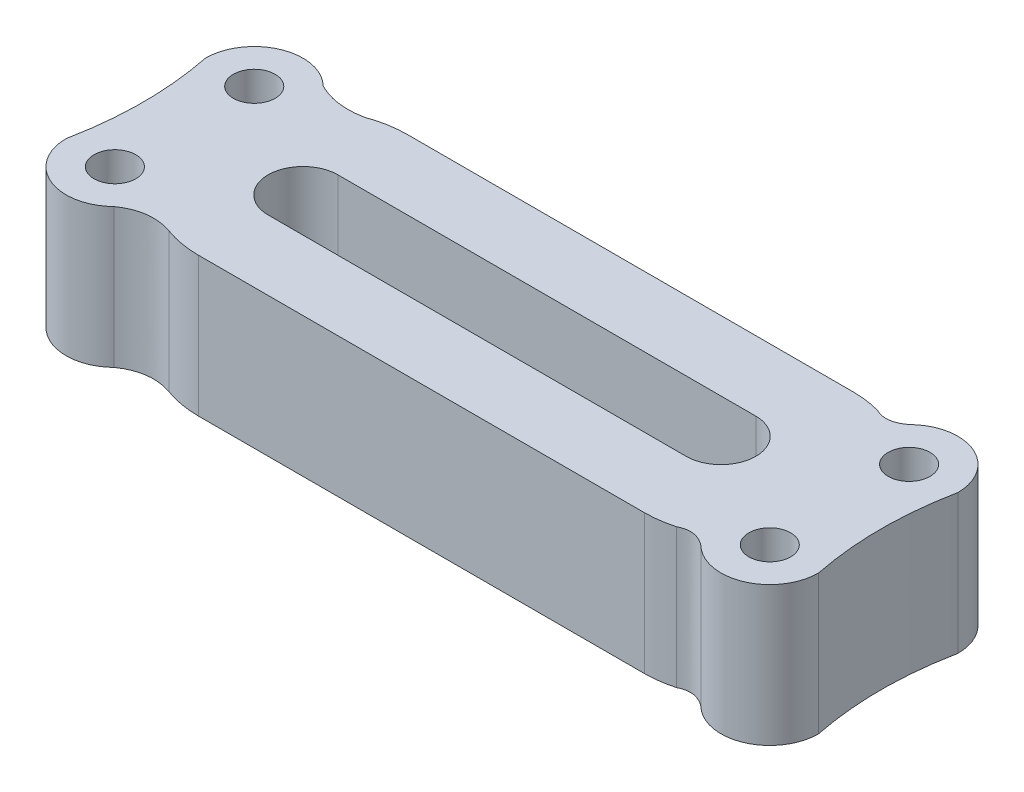
SolidWorks part; units mm, degrees
ref_plane "Płaszczyzna przednia" through (0, 0, 0) normal (0, 0, 1) x (1, 0, 0)
ref_plane "Płaszczyzna górna" through (0, 0, 0) normal (0, 1, 0) x (1, 0, 0)
ref_plane "Płaszczyzna prawa" through (0, 0, 0) normal (1, 0, 0) x (0, 0, -1)
sketch "Szkic1" plane through (0, 0, 0) normal (0, 1, 0) x (1, 0, 0)
  line L0 (-15, 0) -> (15, 0)
  line L2 (-15, 5) -> (15, 5)
  line L3 (-15, 0) -> (-15, -5) construction
  line L4 (-15, -5) -> (17, -5)
  line L5 (-15, 10) -> (17, 10)
  arc A0 (15, 5) -> (15, 0) centre (15, 2.5) cw
  arc A1 (-15, 5) -> (-15, 0) centre (-15, 2.5) ccw
  arc A2 (17, 10) -> (19.0309, 9.7198) centre (17, 2.5) cw
  arc A3 (-15, 10) -> (-17.5874, 9.5396) centre (-15, 2.5) ccw
  circle A4 centre (-23.5, -2.5) radius 1.5
  circle A5 centre (-23.5, 7.5) radius 1.5
  circle A6 centre (23.5, 7.5) radius 1.5
  circle A7 centre (23.5, -2.5) radius 1.5
  arc A8 (-21.0505, 10) -> (-27, 7.5) centre (-23.5, 7.5) ccw
  arc A11 (21.0505, -5) -> (27, -2.5) centre (23.5, -2.5) ccw
  arc A13 (-17.5874, -4.5396) -> (-15, -5) centre (-15, 2.5) ccw
  arc A14 (-27, -2.5) -> (-21.0505, -5) centre (-23.5, -2.5) ccw
  arc A16 (19.0309, -4.7198) -> (17, -5) centre (17, 2.5) cw
  arc A19 (27, 7.5) -> (21.0505, 10) centre (23.5, 7.5) ccw
  spline S0 degree 2 poles (27, -2.5) (26, 2.5) (27, 7.5) knots 0 0 0 1 1 1
  spline S1 degree 2 poles (-27, 7.5) (-26, 2.5) (-27, -2.5) knots 0 0 0 1 1 1
  spline S2 degree 2 poles (-21.0505, -5) (-19.4865, -3.9038) (-17.5874, -4.5396) knots 0 0 0 1 1 1
  spline S3 degree 2 poles (-21.0505, 10) (-19.4285, 9.1564) (-17.5874, 9.5396) knots 0 0 0 1 1 1
  spline S4 degree 2 poles (21.0505, 10) (20.035, 9.2111) (19.0309, 9.7198) knots 0 0 0 1 1 1
  spline S5 degree 2 poles (21.0505, -5) (20.035, -4.2111) (19.0309, -4.7198) knots 0 0 0 1 1 1
  point P4 (0, 0)
  point P10 (0, 5)
  dimension "D1" = 2.5
  dimension "D10" = 3
  dimension "D11" = 3
  dimension "D12" = 3
  dimension "D13" = 3
  dimension "D14" = 7
  dimension "D17" = 7
  dimension "D2" = 30
  dimension "D3" = 5
  dimension "D4" = 5
extrude "Dodanie-wyciągnięcie1" add sketch "Szkic1" along normal blind 10
